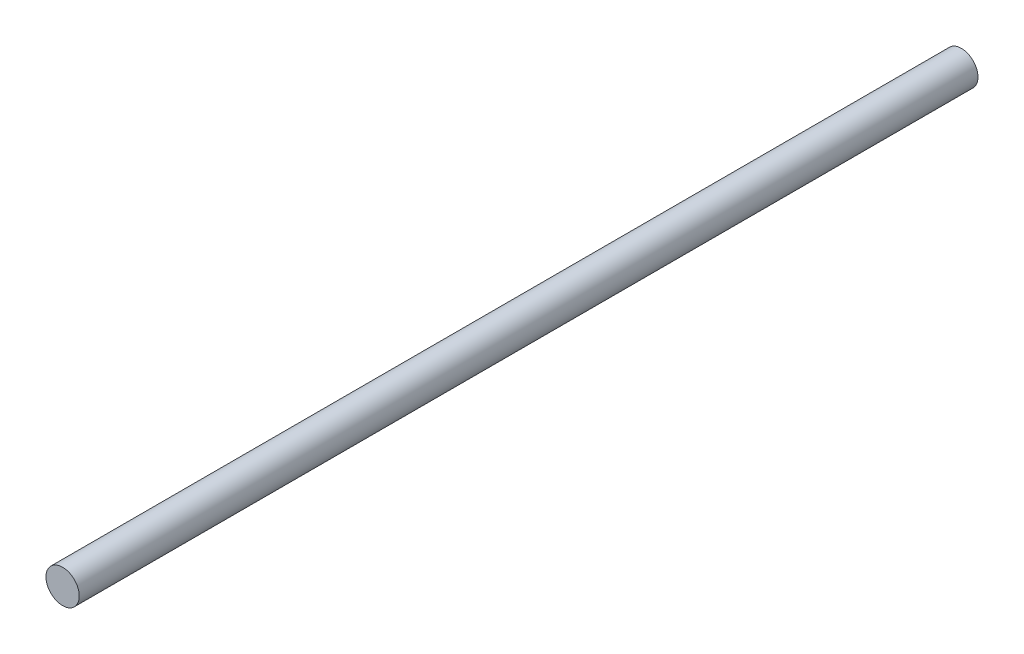
SolidWorks part; units mm, degrees
ref_plane "Front Plane" through (0, 0, 0) normal (0, 0, 1) x (1, 0, 0)
ref_plane "Top Plane" through (0, 0, 0) normal (0, 1, 0) x (1, 0, 0)
ref_plane "Right Plane" through (0, 0, 0) normal (1, 0, 0) x (0, 0, -1)
sketch "Sketch1" plane through (0, 0, 0) normal (0, 0, 1) x (1, 0, 0)
  circle A0 centre (0, 0) radius 3
extrude "Boss-Extrude1" add sketch "Sketch1" along normal blind 162
